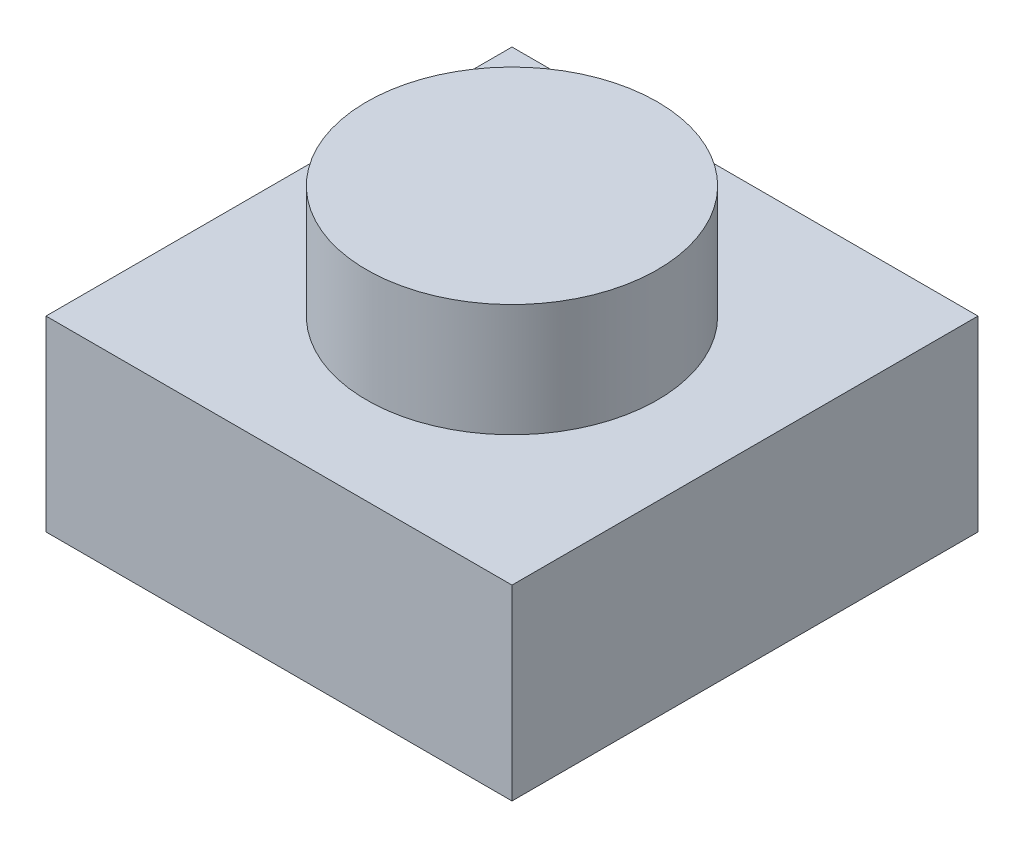
SolidWorks part; units mm, degrees
ref_plane "Front Plane" through (0, 0, 0) normal (0, 0, 1) x (1, 0, 0)
ref_plane "Top Plane" through (0, 0, 0) normal (0, 1, 0) x (1, 0, 0)
ref_plane "Right Plane" through (0, 0, 0) normal (1, 0, 0) x (0, 0, -1)
sketch "Sketch1" plane through (0, 0, 0) normal (0, 1, 0) x (1, 0, 0)
  line L1 (-3.925, 3.925) -> (3.925, 3.925)
  line L2 (-3.925, 3.925) -> (-3.925, -3.925)
  line L3 (-3.925, -3.925) -> (3.925, -3.925)
  line L4 (3.925, 3.925) -> (3.925, -3.925)
  line L5 (-3.925, 3.925) -> (3.925, -3.925) construction
  line L6 (-3.925, -3.925) -> (3.925, 3.925) construction
  point P1 (0, 0)
  dimension "D1" = 7.85
  dimension "D2" = 7.85
extrude "Boss-Extrude1" add sketch "Sketch1" against normal blind 3.15
sketch "Sketch2" plane through (0, 0, 0) normal (0, 1, 0) x (1, 0, 0)
  circle A0 centre (0, 0) radius 2.45
  dimension "D1" = 4.9
extrude "Boss-Extrude2" add sketch "Sketch2" along normal blind 1.9
shell "Shell1" thickness 1.5
